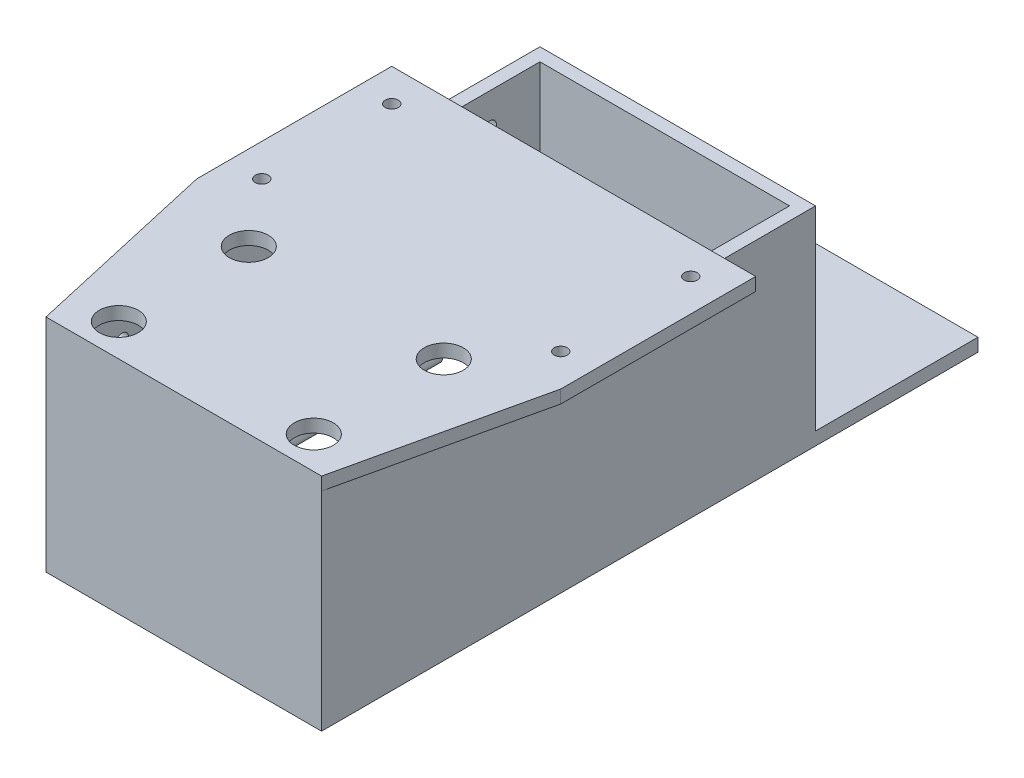
SolidWorks part; units mm, degrees
ref_plane "Front Plane" through (0, 0, 0) normal (0, 0, 1) x (1, 0, 0)
ref_plane "Top Plane" through (0, 0, 0) normal (0, 1, 0) x (1, 0, 0)
ref_plane "Right Plane" through (0, 0, 0) normal (1, 0, 0) x (0, 0, -1)
sketch "Sketch2" plane through (0, 0, 0) normal (0, 1, 0) x (1, 0, 0)
  line L0 (-2, -2) -> (-2, 74)
  line L1 (0, 0) -> (38.4, 0)
  line L2 (0, 0) -> (0, 72)
  line L3 (0, 72) -> (38.4, 72)
  line L4 (38.4, 0) -> (38.4, 72)
  line L5 (-2, 74) -> (40.4, 74)
  line L6 (40.4, -2) -> (40.4, 74)
  line L7 (-2, -2) -> (40.4, -2)
  dimension "D1" = 72
  dimension "D2" = 38.4
  dimension "D3" = 2
extrude "Boss-Extrude4" add sketch "Sketch2" along normal blind 32
sketch "Sketch1" plane through (0, 32, 0) normal (0, 1, 0) x (1, 0, 0)
  line L0 (19.2, 28) -> (19.2, -2) construction
  line L1 (-2, -2) -> (40.4, -2)
  line L2 (-2, -2) -> (-2, 28)
  line L3 (-2, 28) -> (40.4, 28)
  line L4 (40.4, -2) -> (40.4, 28)
  line L5 (-2, 13) -> (40.4, 13) construction
  line L6 (-2, -2) -> (40.4, -2) construction
  line L8 (40.4, -2) -> (40.4, 74) construction
  line L9 (-2, 74) -> (-2, -2) construction
  circle A0 centre (4.2, 3) radius 3
  circle A1 centre (34.2, 3) radius 3
  circle A2 centre (34.2, 23) radius 3
  circle A3 centre (4.2, 23) radius 3
  dimension "D3" = 6
  dimension "D1" = 30
  dimension "D2" = 20
  dimension "D4" = 30
extrude "Boss-Extrude1" add sketch "Sketch1" along normal blind 2
sketch "Sketch4" plane through (0, 32, 0) normal (0, 1, 0) x (1, 0, 0)
  line L0 (-8.8, 43) -> (47.2, 43) construction
  line L1 (47.2, 28) -> (-8.8, 28)
  line L2 (47.2, 28) -> (47.2, 58)
  line L3 (47.2, 58) -> (-8.8, 58)
  line L4 (-8.8, 28) -> (-8.8, 58)
  line L5 (19.2, 58) -> (19.2, 28) construction
  line L6 (40.4, 28) -> (-2, 28) construction
  circle A0 centre (-3.8, 33) radius 1
  circle A1 centre (-3.8, 53) radius 1
  circle A2 centre (42.2, 53) radius 1
  circle A3 centre (42.2, 33) radius 1
  point P18 (0, 0)
  point P19 (0, 0)
  point P20 (19.2, 28)
  dimension "D1" = 2
  dimension "D2" = 20
  dimension "D3" = 46
  dimension "D4" = 30
  dimension "D5" = 56
extrude "Boss-Extrude5" add sketch "Sketch4" along normal blind 2
sketch "Sketch5" plane through (-2, 0, 0) normal (-1, 0, 0) x (0, 0, 1)
  line L0 (2, 34) -> (2, 0) construction
  line L1 (-74, 32) -> (2, 32)
  line L2 (-74, 32) -> (-74, 0)
  line L3 (-74, 0) -> (2, 0)
  line L4 (2, 32) -> (2, 0)
  line L5 (-74, 0) -> (2, 0) construction
  line L6 (2, 16) -> (-74, 16) construction
  line L7 (-36, 32) -> (-36, 0) construction
  circle A0 centre (-7.7, 27) radius 1
  circle A1 centre (-7.7, 5) radius 1
  circle A2 centre (-64.3, 5) radius 1
  circle A3 centre (-64.3, 27) radius 1
  dimension "D1" = 2
  dimension "D2" = 56.6
  dimension "D3" = 22
extrude "Cut-Extrude1" cut sketch "Sketch5" against normal blind 2 contours A1 | A0 | A3 | A2
sketch "Sketch9" plane through (0, 0, 0) normal (1, 0, 0) x (0, 0, -1)
  line L0 (36, 0) -> (36, 32) construction
  line L1 (72, 0) -> (0, 0) construction
  line L2 (58, 32) -> (0, 32) construction
  line L3 (56, 0) -> (56, 1)
  line L4 (56, 0) -> (16, 0)
  line L5 (36, 0) -> (36, 1)
  line L6 (56, 1) -> (16, 1)
  line L7 (16, 0) -> (16, 1)
  dimension "D1" = 1
  dimension "D2" = 20
revolve "Revolve1" add sketch "Sketch9" angle 360 about L6
ref_plane "Plane1" through (19.2, 0, 0) normal (1, 0, 0) x (0, 0, -1)
mirror "Mirror1" about plane through (19.2, 0, 0) normal (1, 0, 0) of "Revolve1"
sketch "Sketch11" plane through (0, 0, -74) normal (0, 0, -1) x (-1, 0, 0)
  line L0 (-40.4, 32) -> (-40.4, 0) construction
  line L1 (2, 0) -> (-40.4, 0)
  line L2 (2, 0) -> (2, 2)
  line L3 (2, 2) -> (-40.4, 2)
  line L4 (-40.4, 0) -> (-40.4, 2)
  line L5 (-19.2, 0) -> (-19.2, -3)
  line L6 (-14.95, -3) -> (-23.45, -3)
  line L7 (-23.45, -3) -> (-23.45, 0)
  line L8 (-23.45, 0) -> (-14.95, 0)
  line L9 (-14.95, -3) -> (-14.95, 0)
  line M5 (-40.4, 0) -> (2, 0)
  line M6 (2, 0) -> (2, 32)
  line M8 (-40.4, 32) -> (-40.4, 0)
  dimension "D1" = 2
  dimension "D2" = 8.5
  dimension "D3" = 3
extrude "Boss-Extrude7" add sketch "Sketch11" along normal blind 25 and the other way up to surface contours L3 L1 M6 M8 M5 | L7 L6 L5 L1 | L6 L9 L1 L5 other way up to face at (19.2, 16, -72)
sketch "Sketch12" plane through (0, 2, 0) normal (0, 1, 0) x (1, 0, 0)
  line L0 (40.4, 86.5) -> (-2, 86.5) construction
  line L1 (40.4, 99) -> (40.4, 74) construction
  line L2 (-2, 99) -> (-2, 74) construction
  line L3 (19.2, 99) -> (19.2, 74) construction
  line L4 (-2, 99) -> (40.4, 99) construction
  line L5 (-2, 74) -> (40.4, 74) construction
  circle A0 centre (19.2, 86.5) radius 2
  dimension "D1" = 4
extrude "Cut-Extrude2" cut sketch "Sketch12" against normal blind 25
chamfer "Chamfer1" distance 1 angle 45 2 edges at (14.95, -3, -85.5) (23.45, -3, -85.5)
sketch "Sketch13" plane through (0, 34, 0) normal (0, 1, 0) x (1, 0, 0)
  line L0 (40.4, -2) -> (47.2, 28)
  line L1 (47.2, 28) -> (40.4, 28)
  line L2 (40.4, 28) -> (40.4, -2)
  line L3 (-8.8, 28) -> (-2, 28)
  line L4 (-2, 28) -> (-2, -2)
  line L5 (-2, -2) -> (-8.8, 28)
extrude "Boss-Extrude8" add sketch "Sketch13" against normal up to surface (2 mm away) up to face at (42.2, 32, -34)
